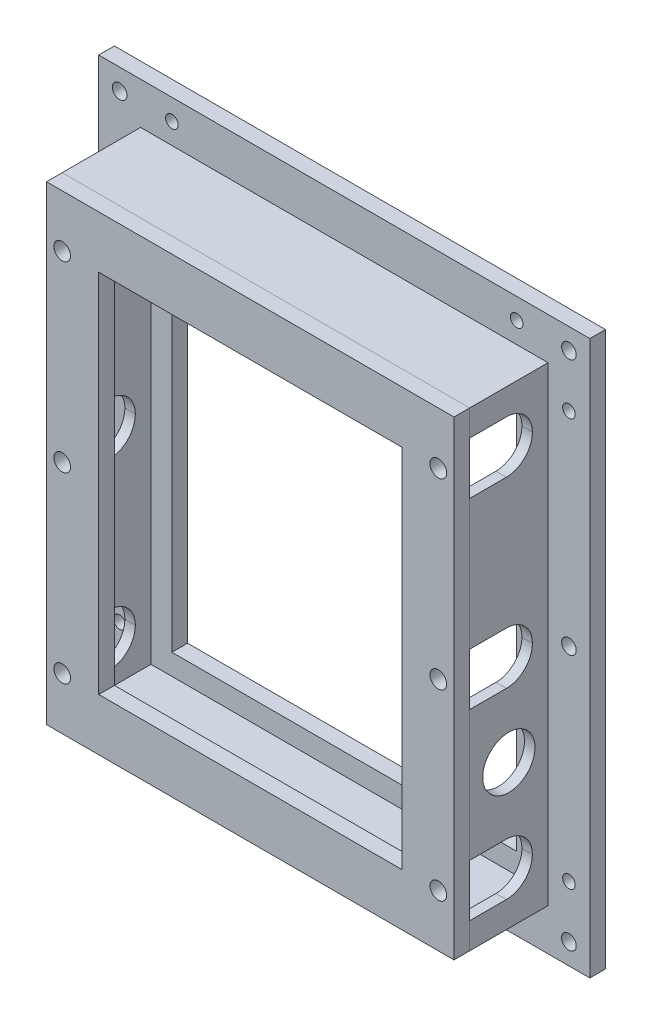
SolidWorks part; units mm, degrees
ref_plane "前视基准面" through (0, 0, 0) normal (0, 0, 1) x (1, 0, 0)
ref_plane "上视基准面" through (0, 0, 0) normal (0, 1, 0) x (1, 0, 0)
ref_plane "右视基准面" through (0, 0, 0) normal (1, 0, 0) x (0, 0, -1)
sketch "草图1" plane through (0, 0, 0) normal (0, 0, 1) x (1, 0, 0)
  line L1 (0, 0) -> (390, 0)
  line L2 (0, 0) -> (0, -450)
  line L3 (0, -450) -> (390, -450)
  line L4 (390, 0) -> (390, -450)
  dimension "D1" = 390
  dimension "D2" = 450
extrude "拉伸1" add sketch "草图1" along normal blind 15
sketch "草图2" plane through (0, 0, 0) normal (0, 0, -1) x (-1, 0, 0)
  line L11 (-390, 0) -> (0, 0)
  line L12 (-390, 0) -> (-390, -450)
  line L13 (-390, -450) -> (0, -450)
  line L14 (-10, -440) -> (-10, -10)
  line L15 (-380, -440) -> (-10, -440)
  line L16 (-380, -10) -> (-380, -440)
  line L17 (-10, -10) -> (-380, -10)
  line L18 (-10, -440) -> (-10, -10)
  line L19 (-380, -440) -> (-10, -440)
  line L20 (-380, -10) -> (-380, -440)
  line L21 (-10, -10) -> (-380, -10)
  line L22 (0, 0) -> (0, -450)
  dimension "D1" = 10
extrude "拉伸2" add sketch "草图2" along normal blind 75 separate body
sketch "草图3" plane through (0, 0, 15) normal (0, 0, 1) x (1, 0, 0)
  line L14 (340, -400) -> (340, -50)
  line L15 (50, -400) -> (340, -400)
  line L16 (50, -50) -> (50, -400)
  line L17 (340, -50) -> (50, -50)
  line L18 (340, -400) -> (340, -50)
  line L19 (50, -400) -> (340, -400)
  line L20 (50, -50) -> (50, -400)
  line L21 (340, -50) -> (50, -50)
  dimension "D1" = 50
extrude "切除-拉伸1" cut sketch "草图3" against normal blind 75
sketch "草图4" plane through (0, 0, -75) normal (0, 0, -1) x (-1, 0, 0)
  line L0 (-30, -30) -> (-360, -30)
  line L1 (-360, -30) -> (-360, -420)
  line L2 (-360, -420) -> (-30, -420)
  line L3 (-30, -420) -> (-30, -30)
  line L8 (-430, 40) -> (-430, -490)
  line L9 (-430, -490) -> (40, -490)
  line L10 (40, -490) -> (40, 40)
  line L11 (40, 40) -> (-430, 40)
  line L12 (-430, 40) -> (-430, -490)
  line L13 (-430, -490) -> (40, -490)
  line L14 (40, -490) -> (40, 40)
  line L15 (40, 40) -> (-430, 40)
  dimension "D1" = 40
  dimension "D2" = 70
extrude "拉伸3" add sketch "草图4" along normal blind 15
sketch "草图5" plane through (0, 0, 15) normal (0, 0, 1) x (1, 0, 0)
  line L7 (15, -50) -> (375, -50) construction
  circle A0 centre (15, -50) radius 8
  circle A1 centre (375, -50) radius 8
  circle A2 centre (15, -225) radius 8
  circle A3 centre (375, -225) radius 8
  circle A4 centre (15, -400) radius 8
  circle A5 centre (375, -400) radius 8
  dimension "D1" = 16
extrude "切除-拉伸2" cut sketch "草图5" against normal blind 30
sketch "草图6" plane through (0, 0, 0) normal (-1, 0, 0) x (0, 0, 1)
  line L0 (0, 0) -> (0, -450) construction
  line L1 (0, -25) -> (-60, -25)
  line L2 (0, -25) -> (0, -75)
  line L3 (0, -75) -> (-60, -75)
  line L4 (-60, -25) -> (-60, -75)
  line L7 (0, -200) -> (-60, -200)
  line L8 (0, -200) -> (0, -250)
  line L9 (0, -250) -> (-60, -250)
  line L10 (-60, -200) -> (-60, -250)
  line L11 (0, -375) -> (-60, -375)
  line L12 (0, -375) -> (0, -425)
  line L13 (0, -425) -> (-60, -425)
  line L14 (-60, -375) -> (-60, -425)
  line L16 (-75, -450) -> (0, -450) construction
  line L17 (-75, 0) -> (0, 0) construction
  dimension "D1" = 50
  dimension "D2" = 25
  dimension "D3" = 60
  dimension "D4" = 25
extrude "切除-拉伸3" cut sketch "草图6" against normal through all
fillet "圆角1" radius 24.9 6 edges at (5, -425, -60) (5, -375, -60) (5, -250, -60) (5, -200, -60) (5, -75, -60) (5, -25, -60)
fillet "圆角2" radius 24.9 6 edges at (385, -75, -60) (385, -25, -60) (385, -375, -60) (385, -425, -60) (385, -250, -60) (385, -200, -60)
sketch "草图7" plane through (0, 0, -75) normal (0, 0, 1) x (1, 0, 0)
  line L0 (-40, -490) -> (-40, 40) construction
  line L1 (430, 40) -> (430, -490) construction
  circle A0 centre (-20, 20) radius 7
  circle A1 centre (410, -420) radius 6
  circle A2 centre (30, 20) radius 6
  circle A3 centre (360, 20) radius 6
  circle A4 centre (-20, -30) radius 6
  circle A5 centre (410, 20) radius 7
  circle A6 centre (-300, 20) radius 6 [skipped]
  circle A7 centre (690, 20) radius 6 [skipped]
  circle A8 centre (-20, -420) radius 6
  circle A9 centre (410, -30) radius 6
  circle A10 centre (-20, -225) radius 7
  circle A13 centre (410, -225) radius 7
  circle A18 centre (-20, -470) radius 7
  circle A19 centre (30, -470) radius 6
  circle A20 centre (360, -470) radius 6
  circle A21 centre (410, -470) radius 7
  circle A22 centre (30, -102.5) radius 6 [skipped]
  circle A23 centre (360, -102.5) radius 6 [skipped]
  circle A24 centre (30, -225) radius 6 [skipped]
  circle A25 centre (360, -225) radius 6 [skipped]
  circle A26 centre (30, -347.5) radius 6 [skipped]
  circle A27 centre (360, -347.5) radius 6 [skipped]
  circle A28 centre (-20, -347.5) radius 7 [skipped]
  circle A29 centre (-20, -102.5) radius 7 [skipped]
  circle A30 centre (410, -102.5) radius 7 [skipped]
  circle A31 centre (410, -347.5) radius 7 [skipped]
  dimension "D2" = 14
  dimension "D3" = 14
  dimension "D1" = 20
  dimension "D4" = 50
  dimension "D5" = 20
  dimension "D6" = 50
  dimension "D7" = 50
  dimension "D8" = 50
  dimension "D9" = 50
  dimension "D10" = 50
extrude "切除-拉伸4" cut sketch "草图7" against normal blind 30
sketch "草图9" plane through (390, 0, 0) normal (1, 0, 0) x (0, 0, -1)
  line L0 (0, -250) -> (0, -375) construction
  circle A0 centre (37.5, -312.5) radius 25
  dimension "D1" = 50
  dimension "D2" = 37.5
extrude "切除-拉伸6" cut sketch "草图9" against normal blind 30
